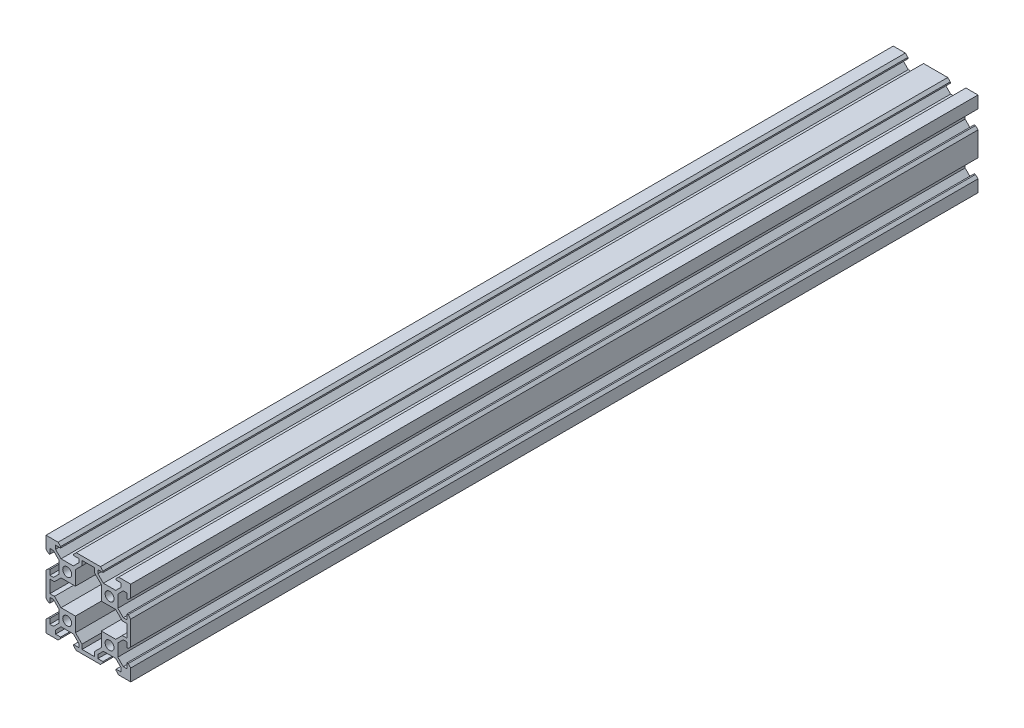
SolidWorks part; units mm, degrees
ref_plane "Front" through (0, 0, 0) normal (0, 0, 1) x (1, 0, 0)
ref_plane "Top" through (0, 0, 0) normal (0, 1, 0) x (1, 0, 0)
ref_plane "Right" through (0, 0, 0) normal (1, 0, 0) x (0, 0, -1)
sketch "草图1" plane through (0, 0, 0) normal (0, 0, 1) x (1, 0, 0)
  line L0 (0, 20) -> (0, -20) construction
  line L1 (-20, -20) -> (20, -20) construction
  line L2 (-20, -20) -> (-20, 20) construction
  line L3 (-20, 20) -> (20, 20) construction
  line L4 (20, -20) -> (20, 20) construction
  line L5 (-20, -20) -> (20, 20) construction
  line L6 (-20, 20) -> (-10, 10) construction
  line L7 (-20, 0) -> (20, 0) construction
  line L8 (5.71, 20) -> (-5.71, 20)
  line L9 (-5.71, 20) -> (-6.9, 18.81)
  line L10 (-6.9, 18.81) -> (-6.9, 18.2)
  line L11 (-6.9, 18.2) -> (-4.5, 18.2)
  line L12 (-4.5, 18.2) -> (-4.5, 16.4899)
  line L13 (-4.5, 16.4899) -> (-7.0899, 13.9)
  line L14 (-7.0899, 13.9) -> (-12.9101, 13.9)
  line L15 (-6.1, 6.1) -> (-6.1, 12.9101)
  line L16 (-6.1, 12.9101) -> (-3, 16.0101)
  line L17 (-3, 16.0101) -> (-3, 18.2)
  line L18 (-3, 18.2) -> (3, 18.2)
  line L19 (-20, 20) -> (-14.29, 20)
  line L20 (-14.29, 20) -> (-13.1, 18.81)
  line L21 (-13.1, 18.81) -> (-13.1, 18.2)
  line L22 (-13.1, 18.2) -> (-15.5, 18.2)
  line L23 (-15.5, 18.2) -> (-15.5, 16.4899)
  line L24 (-15.5, 16.4899) -> (-12.9101, 13.9)
  line L25 (-10, 10) -> (0, 20) construction
  line L26 (-10, 10) -> (-10, 20) construction
  line L27 (-13.9, 6.1) -> (-6.1, 6.1) construction
  line L28 (-13.9, 6.1) -> (-13.9, 13.9) construction
  line L29 (-13.9, 13.9) -> (-6.1, 13.9) construction
  line L30 (-6.1, 6.1) -> (-6.1, 13.9) construction
  line L31 (-13.9, 6.1) -> (-6.1, 13.9) construction
  line L32 (-13.9, 13.9) -> (-10, 10) construction
  line L35 (-10, 10) -> (-6.1, 6.1) construction
  line L37 (-10, 10) -> (20, -20) construction
  line L38 (-16.0101, -3) -> (-18.2, -3)
  line L39 (-20, 20) -> (-20, 14.29)
  line L40 (-20, 14.29) -> (-18.81, 13.1)
  line L41 (-18.81, 13.1) -> (-18.2, 13.1)
  line L42 (-18.2, 13.1) -> (-18.2, 15.5)
  line L43 (-18.2, 15.5) -> (-16.4899, 15.5)
  line L44 (-16.4899, 15.5) -> (-13.9, 12.9101)
  line L45 (-13.9, 7.0899) -> (-13.9, 12.9101)
  line L46 (-16.4899, 4.5) -> (-13.9, 7.0899)
  line L47 (-18.2, 4.5) -> (-16.4899, 4.5)
  line L48 (-18.2, 6.9) -> (-18.2, 4.5)
  line L49 (-18.81, 6.9) -> (-18.2, 6.9)
  line L50 (-20, 5.71) -> (-18.81, 6.9)
  line L51 (-20, -5.71) -> (-20, 5.71)
  line L53 (-18.2, 3) -> (-18.2, -3)
  line L54 (-16.0101, 3) -> (-18.2, 3)
  line L55 (-12.9101, 6.1) -> (-16.0101, 3)
  line L56 (-6.1, 6.1) -> (-12.9101, 6.1)
  line L57 (-12.9101, -6.1) -> (-16.0101, -3)
  line L58 (-6.1, -6.1) -> (-12.9101, -6.1)
  line L59 (-6.1, -6.1) -> (-6.1, -12.9101)
  line L60 (-6.1, -12.9101) -> (-3, -16.0101)
  line L61 (-3, -16.0101) -> (-3, -18.2)
  line L62 (-3, -18.2) -> (3, -18.2)
  line L64 (5.71, -20) -> (-5.71, -20)
  line L65 (-5.71, -20) -> (-6.9, -18.81)
  line L66 (-6.9, -18.81) -> (-6.9, -18.2)
  line L67 (-6.9, -18.2) -> (-4.5, -18.2)
  line L68 (-4.5, -18.2) -> (-4.5, -16.4899)
  line L69 (-4.5, -16.4899) -> (-7.0899, -13.9)
  line L70 (-7.0899, -13.9) -> (-12.9101, -13.9)
  line L71 (-15.5, -16.4899) -> (-12.9101, -13.9)
  line L72 (-15.5, -18.2) -> (-15.5, -16.4899)
  line L73 (-13.1, -18.2) -> (-15.5, -18.2)
  line L74 (-13.1, -18.81) -> (-13.1, -18.2)
  line L75 (-14.29, -20) -> (-13.1, -18.81)
  line L76 (-20, -20) -> (-14.29, -20)
  line L77 (-20, -20) -> (-20, -14.29)
  line L78 (-20, -14.29) -> (-18.81, -13.1)
  line L79 (-18.81, -13.1) -> (-18.2, -13.1)
  line L80 (-18.2, -13.1) -> (-18.2, -15.5)
  line L81 (-18.2, -15.5) -> (-16.4899, -15.5)
  line L82 (-16.4899, -15.5) -> (-13.9, -12.9101)
  line L83 (-13.9, -7.0899) -> (-13.9, -12.9101)
  line L84 (-16.4899, -4.5) -> (-13.9, -7.0899)
  line L85 (-18.2, -4.5) -> (-16.4899, -4.5)
  line L86 (-18.2, -6.9) -> (-18.2, -4.5)
  line L87 (-18.81, -6.9) -> (-18.2, -6.9)
  line L88 (-20, -5.71) -> (-18.81, -6.9)
  line L89 (13.9, 13.9) -> (10, 10) construction
  line L90 (13.9, 6.1) -> (6.1, 13.9) construction
  line L91 (6.1, 6.1) -> (6.1, 13.9) construction
  line L92 (13.9, 13.9) -> (6.1, 13.9) construction
  line L93 (13.9, 6.1) -> (13.9, 13.9) construction
  line L94 (13.9, 6.1) -> (6.1, 6.1) construction
  line L95 (10, 10) -> (10, 20) construction
  line L96 (10, 10) -> (0, 20) construction
  line L97 (20, -5.71) -> (18.81, -6.9)
  line L98 (18.81, -6.9) -> (18.2, -6.9)
  line L99 (18.2, -6.9) -> (18.2, -4.5)
  line L100 (18.2, -4.5) -> (16.4899, -4.5)
  line L101 (16.4899, -4.5) -> (13.9, -7.0899)
  line L102 (13.9, -7.0899) -> (13.9, -12.9101)
  line L103 (16.4899, -15.5) -> (13.9, -12.9101)
  line L104 (18.2, -15.5) -> (16.4899, -15.5)
  line L105 (18.2, -13.1) -> (18.2, -15.5)
  line L106 (18.81, -13.1) -> (18.2, -13.1)
  line L107 (20, -14.29) -> (18.81, -13.1)
  line L108 (20, -20) -> (20, -14.29)
  line L109 (20, -20) -> (14.29, -20)
  line L110 (14.29, -20) -> (13.1, -18.81)
  line L111 (13.1, -18.81) -> (13.1, -18.2)
  line L112 (13.1, -18.2) -> (15.5, -18.2)
  line L113 (15.5, -18.2) -> (15.5, -16.4899)
  line L114 (15.5, -16.4899) -> (12.9101, -13.9)
  line L115 (7.0899, -13.9) -> (12.9101, -13.9)
  line L116 (4.5, -16.4899) -> (7.0899, -13.9)
  line L117 (4.5, -18.2) -> (4.5, -16.4899)
  line L118 (6.9, -18.2) -> (4.5, -18.2)
  line L119 (6.9, -18.81) -> (6.9, -18.2)
  line L120 (5.71, -20) -> (6.9, -18.81)
  line L121 (3, -16.0101) -> (3, -18.2)
  line L122 (6.1, -12.9101) -> (3, -16.0101)
  line L123 (6.1, -6.1) -> (6.1, -12.9101)
  line L124 (6.1, -6.1) -> (12.9101, -6.1)
  line L125 (12.9101, -6.1) -> (16.0101, -3)
  line L126 (6.1, 6.1) -> (12.9101, 6.1)
  line L127 (12.9101, 6.1) -> (16.0101, 3)
  line L128 (16.0101, 3) -> (18.2, 3)
  line L129 (18.2, 3) -> (18.2, -3)
  line L130 (20, -5.71) -> (20, 5.71)
  line L131 (20, 5.71) -> (18.81, 6.9)
  line L132 (18.81, 6.9) -> (18.2, 6.9)
  line L133 (18.2, 6.9) -> (18.2, 4.5)
  line L134 (18.2, 4.5) -> (16.4899, 4.5)
  line L135 (16.4899, 4.5) -> (13.9, 7.0899)
  line L136 (13.9, 7.0899) -> (13.9, 12.9101)
  line L137 (16.4899, 15.5) -> (13.9, 12.9101)
  line L138 (18.2, 15.5) -> (16.4899, 15.5)
  line L139 (18.2, 13.1) -> (18.2, 15.5)
  line L140 (18.81, 13.1) -> (18.2, 13.1)
  line L141 (20, 14.29) -> (18.81, 13.1)
  line L142 (20, 20) -> (20, 14.29)
  line L143 (16.0101, -3) -> (18.2, -3)
  line L144 (15.5, 16.4899) -> (12.9101, 13.9)
  line L145 (15.5, 18.2) -> (15.5, 16.4899)
  line L146 (13.1, 18.2) -> (15.5, 18.2)
  line L147 (13.1, 18.81) -> (13.1, 18.2)
  line L148 (14.29, 20) -> (13.1, 18.81)
  line L149 (20, 20) -> (14.29, 20)
  line L150 (3, 16.0101) -> (3, 18.2)
  line L151 (6.1, 12.9101) -> (3, 16.0101)
  line L152 (6.1, 6.1) -> (6.1, 12.9101)
  line L153 (7.0899, 13.9) -> (12.9101, 13.9)
  line L154 (4.5, 16.4899) -> (7.0899, 13.9)
  line L155 (4.5, 18.2) -> (4.5, 16.4899)
  line L156 (6.9, 18.2) -> (4.5, 18.2)
  line L157 (6.9, 18.81) -> (6.9, 18.2)
  line L158 (5.71, 20) -> (6.9, 18.81)
  circle A0 centre (-10, 10) radius 2.1
  circle A1 centre (-10, -10) radius 2.1
  circle A2 centre (10, -10) radius 2.1
  circle A3 centre (10, 10) radius 2.1
  point P0 (0, 0)
  point P2 (-9.8721, 9.8721)
  point P51 (-18.2, 13.1)
  point P52 (-8.5151, 8.5151)
  point P53 (0, 0)
  point P54 (-11.1081, 11.1081)
  point P55 (-12.7318, 12.7318)
  point P56 (-10.0983, 10.0983)
  point P59 (-18.2, 0)
  point P124 (0, -18.2)
  point P152 (0, 18.2)
  dimension "D10" = 4.2
  dimension "D1" = 40
  dimension "D2" = 6
  dimension "D3" = 1.8
  dimension "D4" = 45
  dimension "D5" = 4.5
  dimension "D6" = 45
  dimension "D7" = 6.2
  dimension "D8" = 0.61
  dimension "D9" = 1.4
  dimension "D12" = 7.8
  dimension "D13" = 1.5
  dimension "D14" = 1.4
  dimension "D15" = 7.8
extrude "凸台-拉伸1" add sketch "草图1" along normal blind 400
